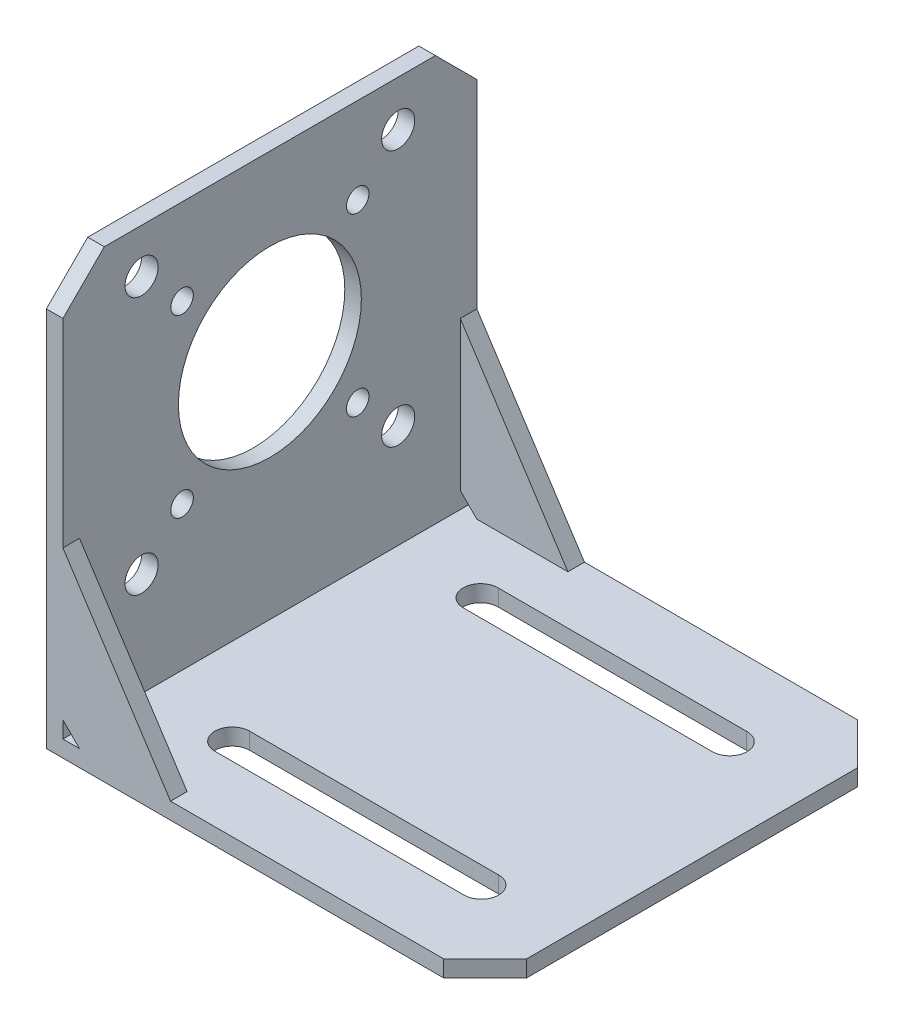
SolidWorks part; units mm, degrees
ref_plane "Front" through (0, 0, 0) normal (0, 0, 1) x (1, 0, 0)
ref_plane "Top" through (0, 0, 0) normal (0, 1, 0) x (1, 0, 0)
ref_plane "Right" through (0, 0, 0) normal (1, 0, 0) x (0, 0, -1)
sketch "Sketch1" plane through (0, 0, 0) normal (0, 0, 1) x (1, 0, 0)
  line L0 (0, 0) -> (0, 51)
  line L1 (0, 51) -> (2, 51)
  line L2 (2, 51) -> (2, 2)
  line L3 (2, 2) -> (53, 2)
  line L4 (53, 2) -> (53, 0)
  line L5 (53, 0) -> (0, 0)
  dimension "D1" = 51
  dimension "D2" = 53
  dimension "D3" = 2
  dimension "D4" = 2
extrude "Boss-Extrude1" add sketch "Sketch1" along normal blind 50
sketch "Sketch2" plane through (2, 0, 0) normal (1, 0, 0) x (0, 0, -1)
  line L0 (-25, 51) -> (-25, 2) construction
  line L1 (-50, 51) -> (0, 51) construction
  line L2 (-50, 2) -> (0, 2) construction
  line L3 (-50, 30) -> (0, 30) construction
  line L4 (-50, 2) -> (-50, 51) construction
  line L5 (0, 2) -> (0, 51) construction
  line L6 (-40.5, 51) -> (-40.5, 2) construction
  line L7 (-9.5, 51) -> (-9.5, 2) construction
  line L8 (-50, 14.5) -> (0, 14.5) construction
  line L9 (-50, 45.5) -> (0, 45.5) construction
  circle A0 centre (-25, 30) radius 11.05
  circle A1 centre (-40.5, 45.6404) radius 2
  circle A2 centre (-9.5, 45.5) radius 2
  circle A3 centre (-40.5, 14.5) radius 2
  circle A4 centre (-9.5, 14.5) radius 2
  dimension "D6" = 4
  dimension "D7" = 4
  dimension "D8" = 4
  dimension "D9" = 4
  dimension "D10" = 22.1
  dimension "D1" = 21
  dimension "D2" = 15.5
  dimension "D3" = 15.5
  dimension "D4" = 15.5
  dimension "D5" = 15.5
extrude "Cut-Extrude1" cut sketch "Sketch2" against normal through all
sketch "Sketch3" plane through (0, 2, 0) normal (0, 1, 0) x (1, 0, 0)
  line L0 (2, -25) -> (53, -25) construction
  line L1 (2, -50) -> (2, 0) construction
  line L2 (53, -50) -> (53, 0) construction
  line L3 (2, -40) -> (53, -40) construction
  line L4 (53, -50) -> (2, -50) construction
  line L5 (27.5, -50) -> (27.5, 0) construction
  line L6 (53, 0) -> (2, 0) construction
  line L7 (2, -10) -> (53, -10) construction
  line L9 (12.4553, -12.1) -> (42.5447, -12.1)
  line L11 (12.5, -7.9005) -> (42.5, -7.9005)
  line L13 (27.5, -7.9005) -> (27.5, -12.1) construction
  line L14 (12.4553, -10) -> (42.5447, -10) construction
  line L15 (12.5, -42.0995) -> (42.5, -42.0995)
  line L17 (12.4553, -37.9) -> (42.5447, -37.9)
  line L19 (27.5, -37.9) -> (27.5, -42.0995) construction
  line L20 (12.4553, -40) -> (42.5447, -40) construction
  arc A0 (42.5, -7.9005) -> (42.5447, -12.1) centre (42.5447, -10) cw
  arc A1 (12.4553, -12.1) -> (12.5, -7.9005) centre (12.4553, -10) cw
  arc A2 (12.5, -42.0995) -> (12.4553, -37.9) centre (12.4553, -40) cw
  arc A3 (42.5447, -37.9) -> (42.5, -42.0995) centre (42.5447, -40) cw
  point P16 (27.5, -10)
  point P20 (27.5, -40)
  dimension "D3" = 2.1
  dimension "D4" = 2.1
  dimension "D5" = 30
  dimension "D6" = 30
  dimension "D7" = 10.4553
  dimension "D8" = 10.4553
  dimension "D1" = 15
  dimension "D2" = 15
extrude "Cut-Extrude2" cut sketch "Sketch3" against normal blind 50
sketch "Sketch5" plane through (0, 0, 50) normal (0, 0, 1) x (1, 0, 0)
  line L0 (2, 22) -> (2, 4)
  line L1 (2, 2) -> (2, 51) construction
  line L2 (2, 4) -> (4, 2)
  line L3 (53, 2) -> (2, 2) construction
  line L4 (4, 2) -> (15, 2)
  line L5 (15, 2) -> (2, 22)
  dimension "D1" = 2
  dimension "D2" = 2
  dimension "D3" = 20
  dimension "D4" = 13
extrude "Boss-Extrude2" add sketch "Sketch5" against normal blind 2
sketch "Sketch6" plane through (0, 0, 0) normal (0, 0, -1) x (-1, 0, 0)
  line L0 (-4, 2) -> (-2, 4)
  line L1 (-2, 2) -> (-53, 2) construction
  line L2 (-2, 51) -> (-2, 2) construction
  line L3 (-2, 4) -> (-2, 22)
  line L4 (-2, 22) -> (-15, 2)
  line L5 (-15, 2) -> (-4, 2)
  dimension "D1" = 2
  dimension "D2" = 20
  dimension "D3" = 2
  dimension "D4" = 13
extrude "Boss-Extrude3" add sketch "Sketch6" against normal blind 2
chamfer "Chamfer1" distance 5 angle 45 4 edges at (53, 1, 0) (53, 1, 50) (1, 51, 0) (1, 51, 50)
sketch "Sketch8" plane through (0, 0, 0) normal (-1, 0, 0) x (0, 0, 1)
  line L0 (25, 30) -> (35.6066, 19.3934) construction
  circle A0 centre (35.6066, 19.3934) radius 1.3612
  circle A1 centre (14.3934, 19.3934) radius 1.3612
  circle A2 centre (14.3934, 40.6066) radius 1.3612
  circle A3 centre (35.6066, 40.6066) radius 1.3612
  point P13 (25, 30)
  dimension "D2" = 2.7223
  dimension "D1" = 15
  dimension "D3" = 4
extrude "Cut-Extrude3" cut sketch "Sketch8" against normal blind 10
